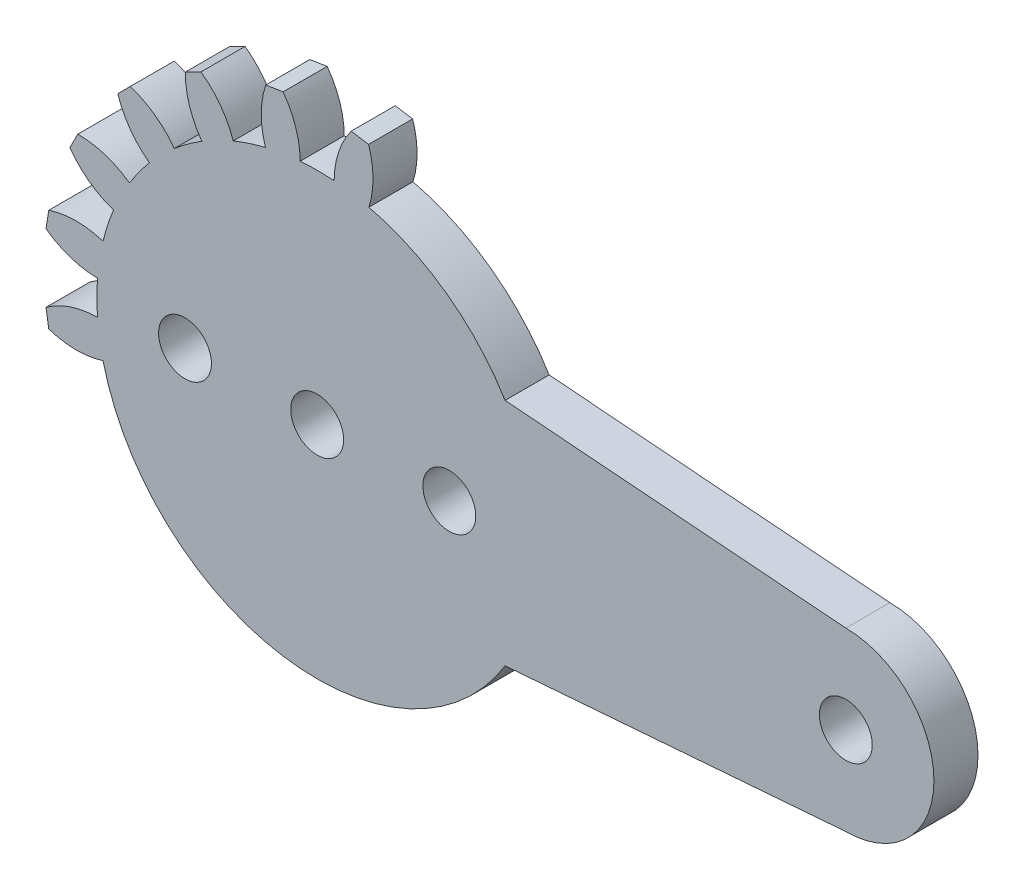
SolidWorks part; units mm, degrees
ref_plane "Front Plane" through (0, 0, 0) normal (0, 0, 1) x (1, 0, 0)
ref_plane "Top Plane" through (0, 0, 0) normal (0, 1, 0) x (1, 0, 0)
ref_plane "Right Plane" through (0, 0, 0) normal (1, 0, 0) x (0, 0, -1)
sketch "Sketch1" plane through (0, 0, 0) normal (0, 0, 1) x (1, 0, 0)
  line L0 (0, 0) -> (30, 0) construction
  line L1 (30, 5) -> (10.6638, 6.5218)
  line L2 (10.6638, 6.5218) -> (-2.4545, 7.5542) construction
  line L3 (-9.5123, 8.1097) -> (-9.5263, 8.1108) construction
  line L4 (30, -5) -> (10.6638, -6.5218)
  line L5 (0, 0) -> (-12.5, 0) construction
  line L6 (0, 0) -> (0, -12.5) construction
  line L7 (0, 0) -> (-4.7898, 14.7414) construction
  line L8 (0, 0) -> (0, 14) construction
  line L9 (0, 0) -> (-2.4247, 15.3092) construction
  line L10 (-2.9186, 15.231) -> (-1.9309, 15.3874)
  line L11 (1.9309, 15.3874) -> (2.9186, 15.231)
  line L12 (6.5913, 14.0376) -> (7.4824, 13.5836) [skipped]
  line L13 (10.6066, 11.3137) -> (11.3137, 10.6066) [skipped]
  line L14 (13.5836, 7.4824) -> (14.0376, 6.5913) [skipped]
  line L15 (15.231, 2.9186) -> (15.3874, 1.9309) [skipped]
  line L16 (15.3874, -1.9309) -> (15.231, -2.9186) [skipped]
  line L17 (14.0376, -6.5913) -> (13.5836, -7.4824) [skipped]
  line L18 (11.3137, -10.6066) -> (10.6066, -11.3137) [skipped]
  line L19 (7.4824, -13.5836) -> (6.5913, -14.0376) [skipped]
  line L20 (2.9186, -15.231) -> (1.9309, -15.3874) [skipped]
  line L21 (-1.9309, -15.3874) -> (-2.9186, -15.231) [skipped]
  line L22 (-6.5913, -14.0376) -> (-7.4824, -13.5836) [skipped]
  line L23 (-10.6066, -11.3137) -> (-11.3137, -10.6066) [skipped]
  line L24 (-13.5836, -7.4824) -> (-14.0376, -6.5913) [skipped]
  line L25 (-15.231, -2.9186) -> (-15.3874, -1.9309)
  line L26 (-15.3874, 1.9309) -> (-15.231, 2.9186)
  line L27 (-14.0376, 6.5913) -> (-13.5836, 7.4824)
  line L28 (-11.3137, 10.6066) -> (-10.6066, 11.3137)
  line L29 (-7.4824, 13.5836) -> (-6.5913, 14.0376)
  line L30 (-2.4545, 7.5542) -> (-9.5123, 8.1097) construction
  line L31 (-9.5263, 8.1108) -> (-11.3101, 8.2512) construction
  line L32 (-11.3101, 8.2512) -> (-26.6541, 9.4588) construction
  arc A0 (-12.1503, -2.9361) -> (10.6638, -6.5218) centre (0, 0) ccw
  circle A1 centre (30, 0) radius 1.5
  circle A2 centre (0, 0) radius 1.5
  arc A3 (30, -5) -> (30, 5) centre (30, 0) ccw
  circle A4 centre (-7.5, 0) radius 1.5
  circle A5 centre (7.5, 0) radius 1.5
  arc A6 (-15.3799, -1.9254) -> (-15.3799, 1.9254) centre (0, 0) ccw construction
  arc A7 (-10.5802, 9.1684) -> (-11.3101, 8.2512) centre (0, 0) ccw construction
  arc A8 (-2.9361, 12.1503) -> (-2.9186, 15.231) centre (1.8294, 13.6636) cw
  arc A9 (-0.9623, 12.4629) -> (-1.9309, 15.3874) centre (-5.9622, 12.4295) ccw
  arc A10 (2.9361, 12.1503) -> (2.9186, 15.231) centre (-1.8294, 13.6636) ccw
  arc A11 (0.9623, 12.4629) -> (1.9309, 15.3874) centre (5.9622, 12.4295) cw
  arc A12 (6.547, 10.6483) -> (7.4824, 13.5836) centre (2.4824, 13.5602) ccw [skipped]
  arc A13 (4.7664, 11.5556) -> (6.5913, 14.0376) centre (9.5113, 9.9788) cw [skipped]
  arc A14 (9.5171, 8.104) -> (11.3137, 10.6066) centre (6.5512, 12.1294) ccw [skipped]
  arc A15 (8.104, 9.5171) -> (10.6066, 11.3137) centre (12.1294, 6.5512) cw [skipped]
  arc A16 (11.5556, 4.7664) -> (14.0376, 6.5913) centre (9.9788, 9.5113) ccw [skipped]
  arc A17 (10.6483, 6.547) -> (13.5836, 7.4824) centre (13.5602, 2.4824) cw [skipped]
  arc A18 (12.4629, 0.9623) -> (15.3874, 1.9309) centre (12.4295, 5.9622) ccw [skipped]
  arc A19 (12.1503, 2.9361) -> (15.231, 2.9186) centre (13.6636, -1.8294) cw [skipped]
  arc A20 (12.1503, -2.9361) -> (15.231, -2.9186) centre (13.6636, 1.8294) ccw [skipped]
  arc A21 (12.4629, -0.9623) -> (15.3874, -1.9309) centre (12.4295, -5.9622) cw [skipped]
  arc A22 (10.6483, -6.547) -> (13.5836, -7.4824) centre (13.5602, -2.4824) ccw [skipped]
  arc A23 (11.5556, -4.7664) -> (14.0376, -6.5913) centre (9.9788, -9.5113) cw [skipped]
  arc A24 (8.104, -9.5171) -> (10.6066, -11.3137) centre (12.1294, -6.5512) ccw [skipped]
  arc A25 (9.5171, -8.104) -> (11.3137, -10.6066) centre (6.5512, -12.1294) cw [skipped]
  arc A26 (4.7664, -11.5556) -> (6.5913, -14.0376) centre (9.5113, -9.9788) ccw [skipped]
  arc A27 (6.547, -10.6483) -> (7.4824, -13.5836) centre (2.4824, -13.5602) cw [skipped]
  arc A28 (0.9623, -12.4629) -> (1.9309, -15.3874) centre (5.9622, -12.4295) ccw [skipped]
  arc A29 (2.9361, -12.1503) -> (2.9186, -15.231) centre (-1.8294, -13.6636) cw [skipped]
  arc A30 (-2.9361, -12.1503) -> (-2.9186, -15.231) centre (1.8294, -13.6636) ccw [skipped]
  arc A31 (-0.9623, -12.4629) -> (-1.9309, -15.3874) centre (-5.9622, -12.4295) cw [skipped]
  arc A32 (-6.547, -10.6483) -> (-7.4824, -13.5836) centre (-2.4824, -13.5602) ccw [skipped]
  arc A33 (-4.7664, -11.5556) -> (-6.5913, -14.0376) centre (-9.5113, -9.9788) cw [skipped]
  arc A34 (-9.5171, -8.104) -> (-11.3137, -10.6066) centre (-6.5512, -12.1294) ccw [skipped]
  arc A35 (-8.104, -9.5171) -> (-10.6066, -11.3137) centre (-12.1294, -6.5512) cw [skipped]
  arc A36 (-11.5556, -4.7664) -> (-14.0376, -6.5913) centre (-9.9788, -9.5113) ccw [skipped]
  arc A37 (-10.6483, -6.547) -> (-13.5836, -7.4824) centre (-13.5602, -2.4824) cw [skipped]
  arc A38 (-12.4629, -0.9623) -> (-15.3874, -1.9309) centre (-12.4295, -5.9622) ccw
  arc A39 (-12.1503, -2.9361) -> (-15.231, -2.9186) centre (-13.6636, 1.8294) cw
  arc A40 (-12.1503, 2.9361) -> (-15.231, 2.9186) centre (-13.6636, -1.8294) ccw
  arc A41 (-12.4629, 0.9623) -> (-15.3874, 1.9309) centre (-12.4295, 5.9622) cw
  arc A42 (-10.6483, 6.547) -> (-13.5836, 7.4824) centre (-13.5602, 2.4824) ccw
  arc A43 (-11.5556, 4.7664) -> (-14.0376, 6.5913) centre (-9.9788, 9.5113) cw
  arc A44 (-8.104, 9.5171) -> (-10.6066, 11.3137) centre (-12.1294, 6.5512) ccw
  arc A45 (-9.5171, 8.104) -> (-11.3137, 10.6066) centre (-6.5512, 12.1294) cw
  arc A46 (-4.7664, 11.5556) -> (-6.5913, 14.0376) centre (-9.5113, 9.9788) ccw
  arc A47 (-6.547, 10.6483) -> (-7.4824, 13.5836) centre (-2.4824, 13.5602) cw
  arc A48 (-12.4629, -0.9623) -> (-12.1503, -2.9361) centre (0, 0) ccw construction
  arc A49 (-12.1503, 2.9361) -> (-12.4629, 0.9623) centre (0, 0) ccw construction
  arc A50 (-12.4629, 0.9623) -> (-12.4629, -0.9623) centre (0, 0) ccw
  arc A51 (-10.6483, 6.547) -> (-11.5556, 4.7664) centre (0, 0) ccw construction
  arc A52 (-11.5556, 4.7664) -> (-12.1503, 2.9361) centre (0, 0) ccw
  arc A53 (-8.104, 9.5171) -> (-9.5123, 8.1097) centre (0, 0) ccw construction
  arc A54 (-9.5171, 8.104) -> (-10.6483, 6.547) centre (0, 0) ccw
  arc A55 (-4.7664, 11.5556) -> (-6.547, 10.6483) centre (0, 0) ccw construction
  arc A56 (-6.547, 10.6483) -> (-8.104, 9.5171) centre (0, 0) ccw
  arc A57 (-1.9554, 12.3461) -> (-2.9361, 12.1503) centre (0, 0) ccw construction
  arc A58 (-2.9361, 12.1503) -> (-4.7664, 11.5556) centre (0, 0) ccw
  arc A59 (2.9361, 12.1503) -> (0.9623, 12.4629) centre (0, 0) ccw construction
  arc A60 (0.9623, 12.4629) -> (-0.9623, 12.4629) centre (0, 0) ccw
  arc A61 (-7.2292, 11.9891) -> (-9.1684, 10.5802) centre (0, 0) ccw construction
  arc A62 (-9.1684, 10.5802) -> (-10.5802, 9.1684) centre (0, 0) ccw construction
  arc A63 (-11.3101, 8.2512) -> (-11.9891, 7.2292) centre (0, 0) ccw construction
  arc A64 (-13.6363, 3.1705) -> (-13.9486, 1.1985) centre (0, 0) ccw construction
  arc A65 (-11.9891, 7.2292) -> (-12.8956, 5.4502) centre (0, 0) ccw construction
  arc A66 (-13.9486, 1.1985) -> (-13.9486, -1.1985) centre (0, 0) ccw construction
  arc A67 (-13.9486, -1.1985) -> (-13.6363, -3.1705) centre (0, 0) ccw construction
  arc A68 (-15.3799, 1.9254) -> (-15.3799, -1.9254) centre (0, 0) ccw construction
  arc A69 (-13.6363, -3.1705) -> (12.4616, -6.3803) centre (0, 0) ccw construction
  arc A70 (-2.1901, 13.8276) -> (-3.1705, 13.6363) centre (0, 0) ccw construction
  arc A71 (12.4616, -6.3803) -> (14, 0) centre (0, 0) ccw construction
  arc A72 (10.6638, -6.5218) -> (12.5, 0) centre (0, 0) ccw construction
  arc A73 (10.6638, 6.5218) -> (2.9361, 12.1503) centre (0, 0) ccw
  arc A74 (14, 0) -> (12.4616, 6.3803) centre (0, 0) ccw construction
  arc A75 (12.4616, 6.3803) -> (3.1705, 13.6363) centre (0, 0) ccw construction
  arc A76 (3.1705, 13.6363) -> (1.1985, 13.9486) centre (0, 0) ccw construction
  arc A77 (1.1985, 13.9486) -> (0, 14) centre (0, 0) ccw construction
  arc A78 (0, 14) -> (-1.1985, 13.9486) centre (0, 0) ccw construction
  arc A79 (-1.1985, 13.9486) -> (-2.1901, 13.8276) centre (0, 0) ccw construction
  arc A80 (-0.9623, 12.4629) -> (-1.9554, 12.3461) centre (0, 0) ccw construction
  arc A81 (-3.1705, 13.6363) -> (-4.3262, 13.3148) centre (0, 0) ccw construction
  arc A82 (-5.4502, 12.8956) -> (-7.2292, 11.9891) centre (0, 0) ccw construction
  arc A83 (-4.3262, 13.3148) -> (-5.4502, 12.8956) centre (0, 0) ccw construction
  arc A84 (12.5, 0) -> (10.6638, 6.5218) centre (0, 0) ccw construction
  arc A85 (-9.5123, 8.1097) -> (-9.5171, 8.104) centre (0, 0) ccw construction
  arc A86 (-12.8956, 5.4502) -> (-13.6363, 3.1705) centre (0, 0) ccw construction
  arc A87 (25, 0) -> (30, -5) centre (30, 0) ccw construction
  arc A88 (30, 5) -> (25, 0) centre (30, 0) ccw construction
  point P21 (-1.9554, 12.3461)
  point P27 (-2.4247, 15.3092)
  point P149 (0, 0)
  dimension "D1" = 25
  dimension "D2" = 3
  dimension "D3" = 10
  dimension "D5" = 3
  dimension "D7" = 31
  dimension "D8" = 28
  dimension "D13" = 5
  dimension "30" = 30
  dimension "D4" = 4.5
  dimension "D6" = 7.5
  dimension "D9" = 18
  dimension "D10" = 9
  dimension "D11" = 1
  dimension "D12" = 1
  dimension "D14" = 20
extrude "Boss-Extrude1" add sketch "Sketch1" along normal blind 2.5
sketch "Sketch2" plane through (0, 0, 2.5) normal (0, 0, 1) x (1, 0, 0)
  circle A1 centre (0, 0) radius 15.5081 construction
